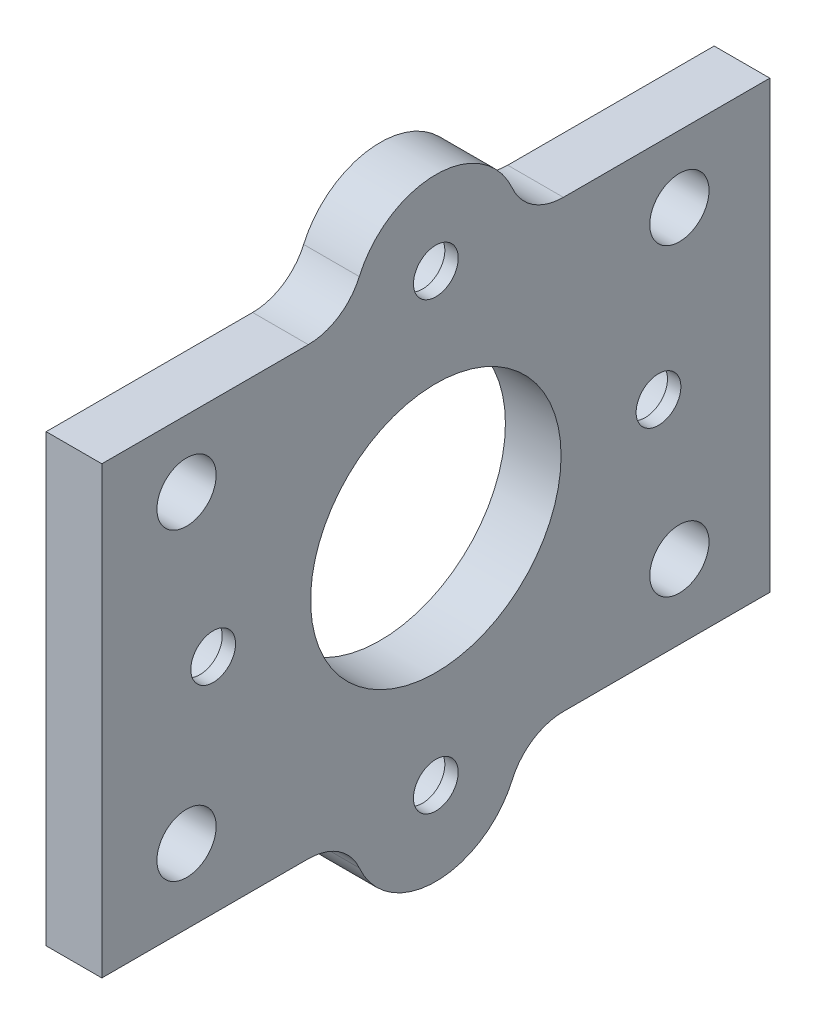
SolidWorks part; units mm, degrees
ref_plane "Front" through (0, 0, 0) normal (0, 0, 1) x (1, 0, 0)
ref_plane "Top" through (0, 0, 0) normal (0, 1, 0) x (1, 0, 0)
ref_plane "Right" through (0, 0, 0) normal (1, 0, 0) x (0, 0, -1)
sketch "Sketch1" plane through (0, 0, 0) normal (1, 0, 0) x (0, 0, -1)
  line L0 (52.6497, 50.8) -> (76.2, 50.8)
  line L1 (0, 0) -> (23.5503, 0)
  line L2 (0, 0) -> (0, 50.8)
  line L3 (0, 50.8) -> (23.5503, 50.8)
  line L4 (76.2, 0) -> (76.2, 50.8)
  line L5 (52.6497, 0) -> (76.2, 0)
  arc A0 (29.3702, 54.61) -> (46.8298, 54.61) centre (38.1, 50.8) cw
  arc A1 (29.3702, -3.81) -> (46.8298, -3.81) centre (38.1, 0) ccw
  arc A2 (29.3702, -3.81) -> (23.5503, 0) centre (23.5503, -6.35) ccw
  arc A3 (46.8298, -3.81) -> (52.6497, 0) centre (52.6497, -6.35) cw
  arc A4 (46.8298, 54.61) -> (52.6497, 50.8) centre (52.6497, 57.15) ccw
  arc A5 (29.3702, 54.61) -> (23.5503, 50.8) centre (23.5503, 57.15) cw
  point P11 (0, 0)
  point P12 (0, 0)
  point P13 (0, 0)
  point P18 (47.625, 0)
  point P21 (47.625, 50.8)
  dimension "D3" = 9.525
  dimension "D4" = 38.1
  dimension "D5" = 6.35
  dimension "D1" = 76.2
  dimension "D2" = 50.8
extrude "Boss-Extrude1" add sketch "Sketch1" along normal blind 6.35
sketch "Sketch2" plane through (6.35, 0, 0) normal (1, 0, 0) x (0, 0, -1)
  circle A0 centre (38.1, 25.4) radius 14.2875
  dimension "D1" = 28.575
  dimension "D2" = 38.1
  dimension "D3" = 25.4
extrude "Cut-Extrude1" cut sketch "Sketch2" against normal through all
hole_wizard "CBORE for #10 Socket Head Cap Screw1" positions "Sketch3" profile "Sketch4" counterbore size "#10" standard "ANSI Inch" end condition through all
sketch "Sketch3" plane through (0, 0, 0) normal (-1, 0, 0) x (0, 0, 1)
  circle A0 centre (-38.1, 25.4) radius 25.4 construction
  point P0 (-63.5, 25.4)
  point P14 (-38.1, 50.8)
  point P15 (-12.7, 25.4)
  point P16 (-38.1, 0)
  point P18 (-38.1, 0)
  dimension "D1" = 50.8
  dimension "D2" = 4
sketch "Sketch4" plane through (0, 25.4, -63.5) normal (0, 1, 0) x (0, 0, 1)
  line L0 (0, 0) -> (0, 6.35)
  line L1 (0, 6.35) -> (2.5527, 6.35)
  line L3 (2.5527, 6.35) -> (2.5527, 4.826)
  line L4 (2.5527, 4.826) -> (4.7625, 4.826)
  line L5 (4.7625, 4.826) -> (4.7625, 0)
  line L7 (4.7625, 0) -> (0, 0)
  line L11 (0, -6.35) -> (0, 107.95) construction
  dimension "Thru Hole Dia." = 5.1054
  dimension "Thru Hole Depth" = 6.35
  dimension "C'Bore Dia." = 9.525
  dimension "C'Bore Depth" = 4.826
hole_wizard "1/4 Clearance Hole1" positions "Sketch5" profile "Sketch6" hole size "1/4" standard "ANSI Inch" end condition through all
sketch "Sketch5" plane through (6.35, 0, 0) normal (1, 0, 0) x (0, 0, -1)
  point P0 (9.6611, 43.1743)
  point P2 (65.884, 43.1743)
  point P4 (65.884, 8.4676)
  point P6 (9.6611, 8.4676)
sketch "Sketch6" plane through (6.35, 43.1743, -9.6611) normal (0, 1, 0) x (0, 0, -1)
  line L0 (0, 0) -> (0, 6.35)
  line L1 (0, 6.35) -> (3.3782, 6.35)
  line L2 (3.3782, 6.35) -> (3.3782, 0)
  line L5 (3.3782, 0) -> (0, 0)
  line L11 (0, -6.35) -> (0, 107.95) construction
  dimension "Thru Hole Dia." = 6.7564
  dimension "Thru Hole Depth" = 6.35
